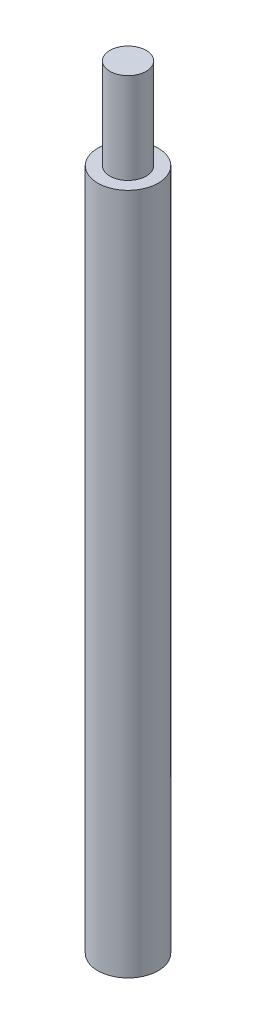
SolidWorks part; units mm, degrees
ref_plane "Front Plane" through (0, 0, 0) normal (0, 0, 1) x (1, 0, 0)
ref_plane "Top Plane" through (0, 0, 0) normal (0, 1, 0) x (1, 0, 0)
ref_plane "Right Plane" through (0, 0, 0) normal (1, 0, 0) x (0, 0, -1)
sketch "Sketch1" plane through (0, 0, 0) normal (0, 1, 0) x (1, 0, 0)
  circle A0 centre (0, 0) radius 10
  dimension "D1" = 20
extrude "Boss-Extrude1" add sketch "Sketch1" along normal blind 225.425
sketch "Sketch2" plane through (0, 225.425, 0) normal (0, 1, 0) x (1, 0, 0)
  circle A0 centre (0, 0) radius 6
  dimension "D1" = 12
extrude "Boss-Extrude2" add sketch "Sketch2" along normal blind 30
